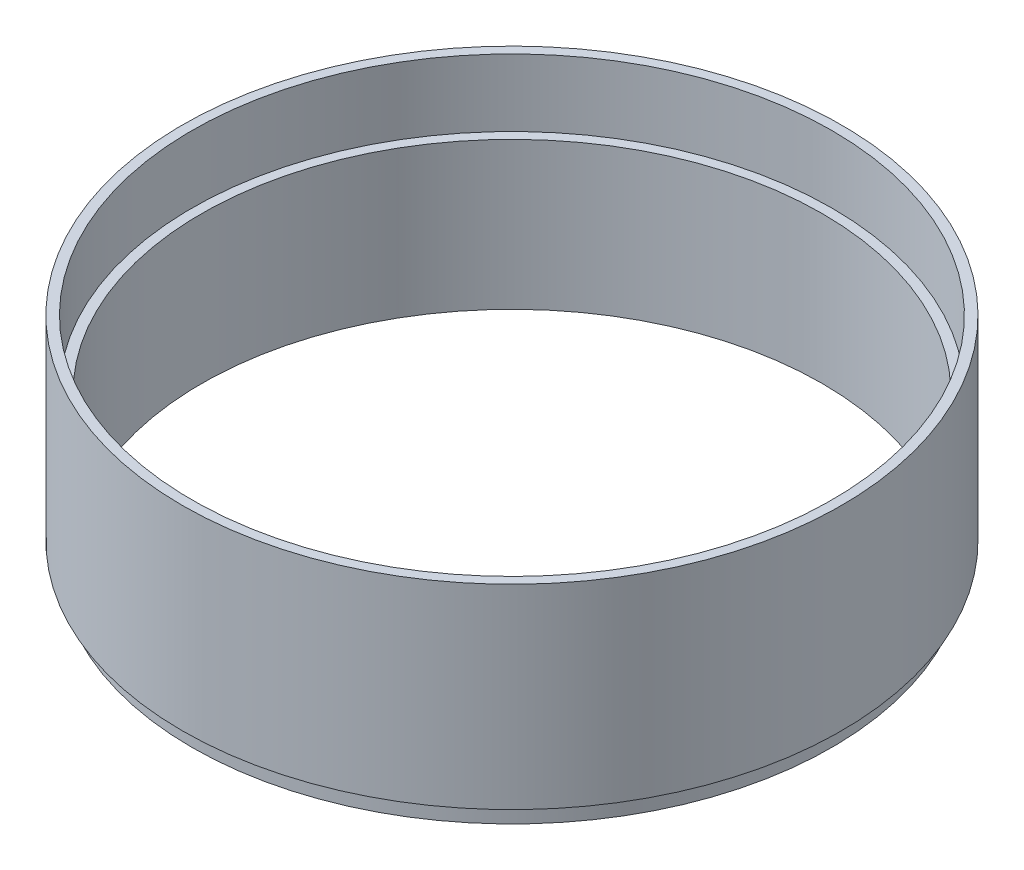
SolidWorks part; units mm, degrees
ref_plane "前视基准面" through (0, 0, 0) normal (0, 0, 1) x (1, 0, 0)
ref_plane "上视基准面" through (0, 0, 0) normal (0, 1, 0) x (1, 0, 0)
ref_plane "右视基准面" through (0, 0, 0) normal (1, 0, 0) x (0, 0, -1)
other "Configuration Table"
sketch "草图1" plane through (0, 0, 0) normal (0, 1, 0) x (1, 0, 0)
  circle A0 centre (0, 0) radius 100
  circle A1 centre (0, 0) radius 97
  dimension "D1" = 200
  dimension "D2" = 194
extrude "凸台-拉伸1" add sketch "草图1" along normal blind 6
sketch "草图2" plane through (0, 6, 0) normal (0, 1, 0) x (1, 0, 0)
  circle A0 centre (0, 0) radius 103
  circle A1 centre (0, 0) radius 97
  dimension "D1" = 206
  dimension "D2" = 194
extrude "凸台-拉伸2" add sketch "草图2" along normal blind 40
sketch "草图3" plane through (0, 46, 0) normal (0, 1, 0) x (1, 0, 0)
  circle A0 centre (0, 0) radius 103
  circle A1 centre (0, 0) radius 100
  dimension "D1" = 206
  dimension "D2" = 200
extrude "凸台-拉伸3" add sketch "草图3" along normal blind 21
